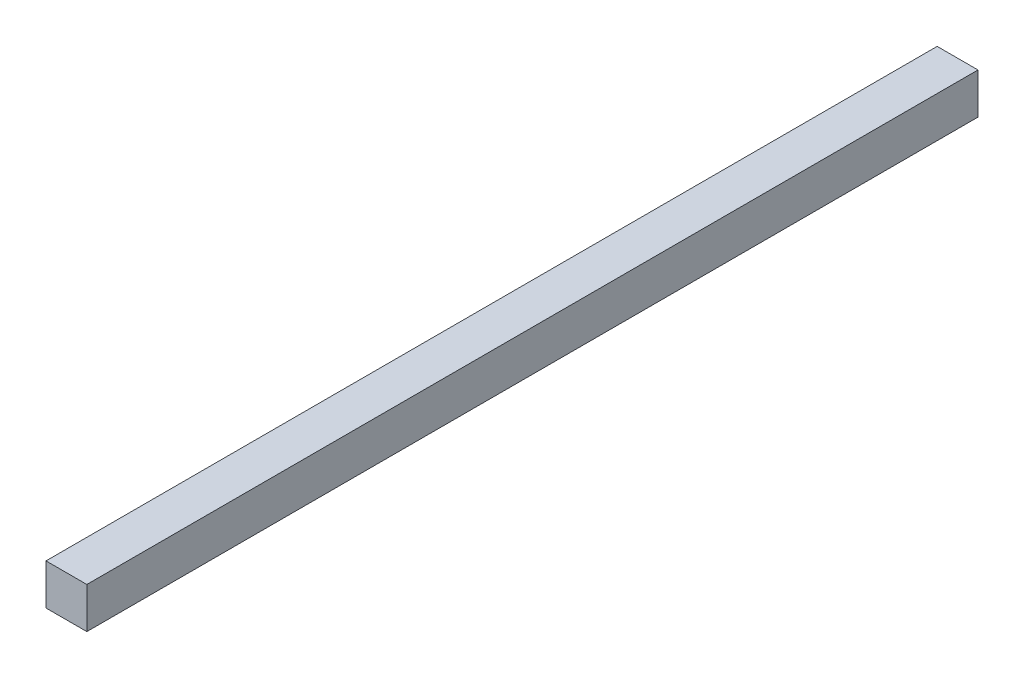
SolidWorks part; units mm, degrees
ref_plane "Front Plane" through (0, 0, 0) normal (0, 0, 1) x (1, 0, 0)
ref_plane "Top Plane" through (0, 0, 0) normal (0, 1, 0) x (1, 0, 0)
ref_plane "Right Plane" through (0, 0, 0) normal (1, 0, 0) x (0, 0, -1)
sketch "Sketch1" plane through (0, 0, 0) normal (0, 0, 1) x (1, 0, 0)
  line L0 (0, 17.4625) -> (0, -17.4625)
  line L1 (-17.4625, 0) -> (17.4625, 0) construction
  point P6 (0, 0)
  dimension "Width" = 34.925
  dimension "Thk" = 34.925
sketch "Sketch2" plane through (0, 0, 0) normal (1, 0, 0) x (0, 0, -1)
  line L0 (457.2, 0) -> (-457.2, 0)
  point P4 (0, 0)
  dimension "Length" = 914.4
sketch "Sketch3" plane through (0, 0, 0) normal (0, 0, 1) x (1, 0, 0)
  line L1 (17.4625, 17.4625) -> (-17.4625, 17.4625)
  line L2 (17.4625, 17.4625) -> (17.4625, -17.4625)
  line L3 (17.4625, -17.4625) -> (-17.4625, -17.4625)
  line L4 (-17.4625, 17.4625) -> (-17.4625, -17.4625)
  line L5 (17.4625, 17.4625) -> (-17.4625, -17.4625) construction
  line L6 (17.4625, -17.4625) -> (-17.4625, 17.4625) construction
  point P0 (0, 0)
extrude "Boss-Extrude1" add sketch "Sketch3" along normal blind 762
